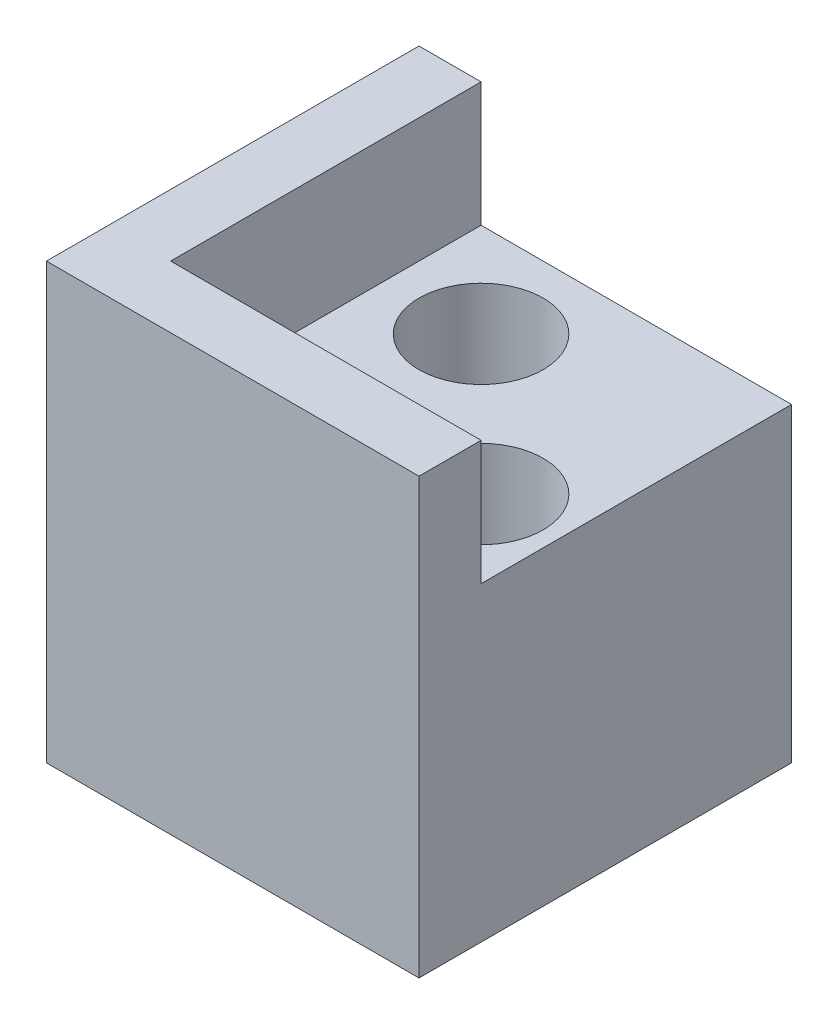
SolidWorks part; units mm, degrees
ref_plane "Front Plane" through (0, 0, 0) normal (0, 0, 1) x (1, 0, 0)
ref_plane "Top Plane" through (0, 0, 0) normal (0, 1, 0) x (1, 0, 0)
ref_plane "Right Plane" through (0, 0, 0) normal (1, 0, 0) x (0, 0, -1)
sketch "Sketch1" plane through (0, 0, 0) normal (0, 1, 0) x (1, 0, 0)
  line L1 (-15, 15) -> (15, 15)
  line L2 (-15, 15) -> (-15, -15)
  line L3 (-15, -15) -> (15, -15)
  line L4 (15, 15) -> (15, -15)
  line L5 (-15, 15) -> (15, -15) construction
  line L6 (-15, -15) -> (15, 15) construction
  point P0 (0, 0)
  dimension "D1" = 30
  dimension "D2" = 30
extrude "Boss-Extrude2" add sketch "Sketch1" along normal blind 35
sketch "Sketch2" plane through (0, 35, 0) normal (0, 1, 0) x (1, 0, 0)
  line L1 (15, 15) -> (-10, 15)
  line L2 (15, 15) -> (15, -10)
  line L3 (15, -10) -> (-10, -10)
  line L4 (-10, 15) -> (-10, -10)
  dimension "D1" = 25
  dimension "D2" = 25
extrude "Cut-Extrude1" cut sketch "Sketch2" against normal blind 10
sketch "Sketch3" plane through (0, 25, 0) normal (0, 1, 0) x (1, 0, 0)
  line L0 (-10, 15) -> (15, -10) construction
  line L1 (15, -10) -> (2.5, 2.5) construction
  line L2 (-2.4229, 7.4229) -> (8.75, -3.75) construction
  circle A0 centre (8.75, -3.75) radius 2
  circle A1 centre (-2.4229, 7.4229) radius 2
  circle A2 centre (-2.4229, 7.4229) radius 5
  circle A3 centre (8.75, -3.75) radius 5
  dimension "D1" = 4
  dimension "D2" = 10
  dimension "D3" = 10
  dimension "D4" = 4
extrude "Cut-Extrude4" cut sketch "Sketch3" against normal blind 20
sketch "Sketch5" plane through (0, 25, 0) normal (0, 1, 0) x (1, 0, 0)
  circle A0 centre (-2.4229, 7.4229) radius 2
  circle A1 centre (8.75, -3.75) radius 2
extrude "Cut-Extrude5" cut sketch "Sketch5" against normal blind 25
